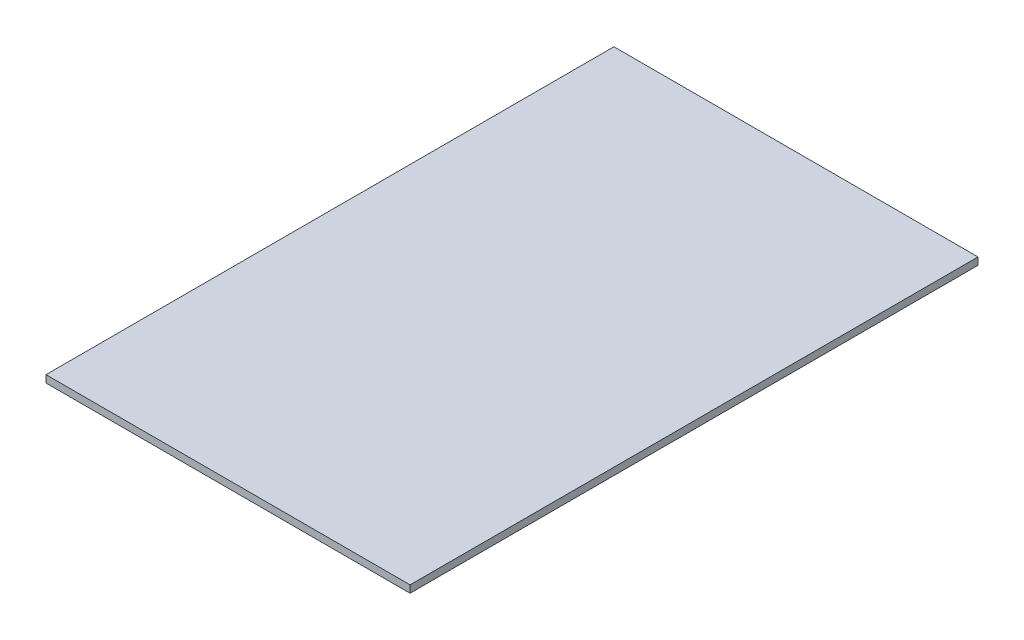
SolidWorks part; units mm, degrees
ref_plane "Front Plane" through (0, 0, 0) normal (0, 0, 1) x (1, 0, 0)
ref_plane "Top Plane" through (0, 0, 0) normal (0, 1, 0) x (1, 0, 0)
ref_plane "Right Plane" through (0, 0, 0) normal (1, 0, 0) x (0, 0, -1)
sketch "Sketch1" plane through (0, 0, 0) normal (0, 1, 0) x (1, 0, 0)
  line L1 (-158.75, -247.65) -> (158.75, -247.65)
  line L2 (-158.75, -247.65) -> (-158.75, 247.65)
  line L3 (-158.75, 247.65) -> (158.75, 247.65)
  line L4 (158.75, -247.65) -> (158.75, 247.65)
  line L5 (-158.75, -247.65) -> (158.75, 247.65) construction
  line L6 (-158.75, 247.65) -> (158.75, -247.65) construction
  point P0 (0, 0)
  dimension "D1" = 495.3
  dimension "D2" = 317.5
extrude "Boss-Extrude1" add sketch "Sketch1" along normal blind 6.35
